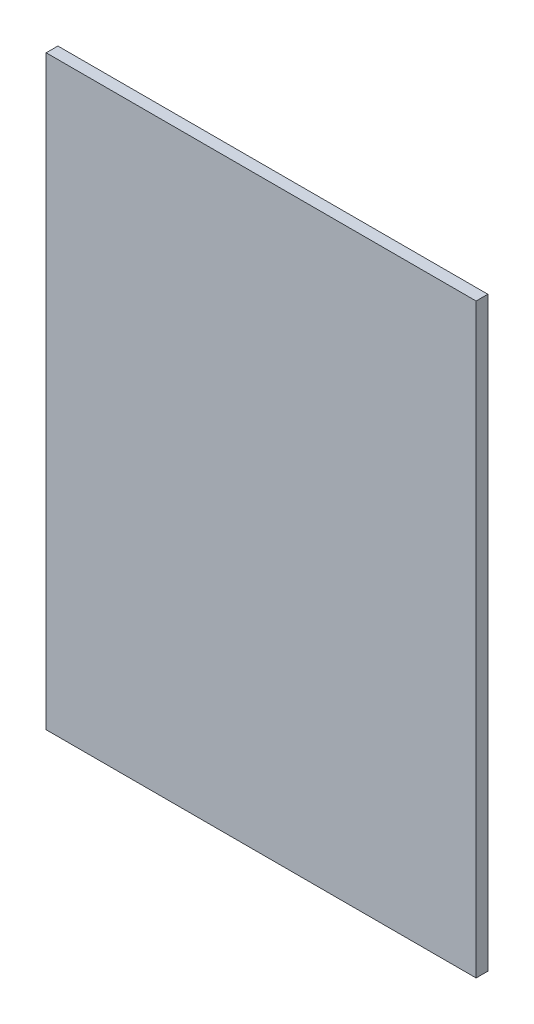
SolidWorks part; units mm, degrees
material "Beryllium Copper, UNS C17000"
ref_plane "Front Plane" through (0, 0, 0) normal (0, 0, 1) x (1, 0, 0)
ref_plane "Top Plane" through (0, 0, 0) normal (0, 1, 0) x (1, 0, 0)
ref_plane "Right Plane" through (0, 0, 0) normal (1, 0, 0) x (0, 0, -1)
sketch "Sketch1" plane through (0, 0, 0) normal (0, 0, 1) x (1, 0, 0)
  line L1 (-40.6667, 114.3333) -> (69.3333, 114.3333)
  line L2 (-40.6667, 114.3333) -> (-40.6667, -35.6667)
  line L3 (-40.6667, -35.6667) -> (69.3333, -35.6667)
  line L4 (69.3333, 114.3333) -> (69.3333, -35.6667)
  dimension "D1" = 110
  dimension "D2" = 150
extrude "Boss-Extrude1" add sketch "Sketch1" along normal blind 3
